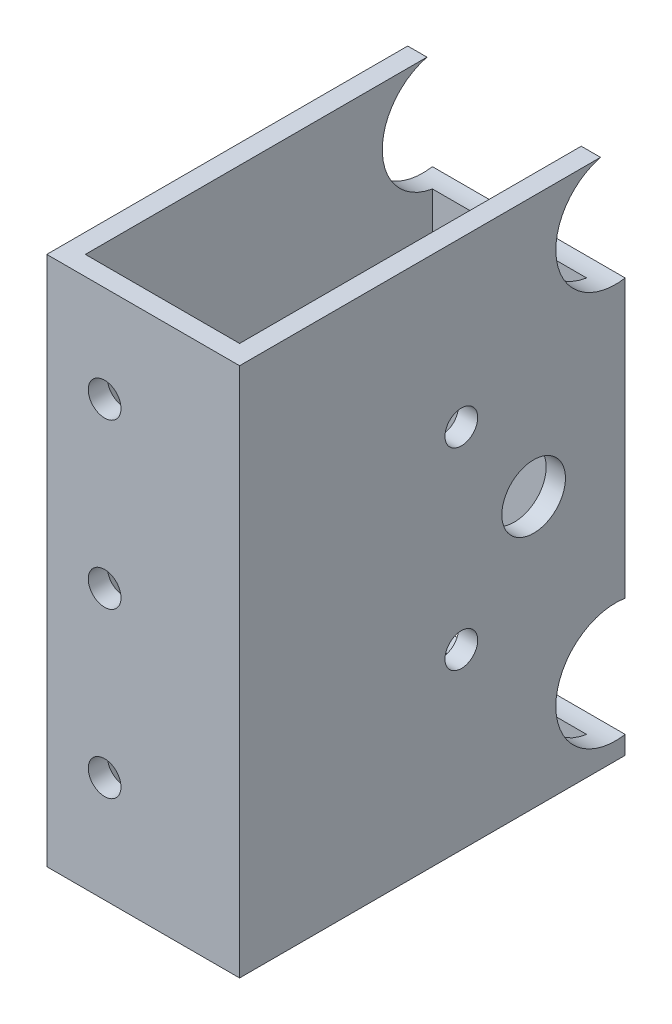
SolidWorks part; units mm, degrees
other "Preload Steel Carriage Core"
other "Preload Steel Carriage Core Left"
ref_plane "Front Plane" through (0, 0, 0) normal (0, 0, 1) x (1, 0, 0)
ref_plane "Top Plane" through (0, 0, 0) normal (0, 1, 0) x (1, 0, 0)
ref_plane "Right Plane" through (0, 0, 0) normal (1, 0, 0) x (0, 0, -1)
sketch3d "Steel tube stock sketch datum points"
  point P0 (29.7083, -56, -29)
  point P1 (39.7083, -56, -29)
  point P2 (29.7083, -46, -29)
ref_plane "Steel tube stock sketch plane" through (0, 0, -29) normal (0, 0, 1) x (1, 0, 0)
sketch "Steel tube stock sketch" plane through (0, 0, -29) normal (0, 0, 1) x (1, 0, 0)
  line L0 (29.7083, -56) -> (49.7083, -56)
  line L1 (49.7083, -56) -> (49.7083, -1)
  line L2 (49.7083, -1) -> (29.7083, -1)
  line L3 (29.7083, -1) -> (29.7083, -56)
extrude "Steel tube stock" add sketch "Steel tube stock sketch" along normal blind 40 separate body
sketch3d "Tube interior sketch datum points"
  point P0 (31.7083, -56.1, -27)
  point P1 (41.7083, -56.1, -27)
  point P2 (31.7083, -46.1, -27)
ref_plane "Tube interior sketch plane" through (0, 0, -27) normal (0, 0, 1) x (1, 0, 0)
sketch "Tube interior sketch" plane through (0, 0, -27) normal (0, 0, 1) x (1, 0, 0)
  line L0 (31.7083, -56.1) -> (47.7083, -56.1)
  line L1 (47.7083, -56.1) -> (47.7083, -0.9)
  line L2 (47.7083, -0.9) -> (31.7083, -0.9)
  line L3 (31.7083, -0.9) -> (31.7083, -56.1)
extrude "Tube interior" cut sketch "Tube interior sketch" along normal blind 36
sketch3d "Guide bush clearance 1 sketch datum points"
  point P0 (29.6, -9, -28)
  point P1 (29.6, 1, -28)
  point P2 (29.6, -9, -18)
ref_plane "Guide bush clearance 1 sketch plane" through (29.6, 0, 0) normal (1, 0, 0) x (0, 0, -1)
sketch "Guide bush clearance 1 sketch" plane through (29.6, 0, 0) normal (1, 0, 0) x (0, 0, -1)
  circle A0 centre (28, -9) radius 6.2
extrude "Guide bush clearance 1" cut sketch "Guide bush clearance 1 sketch" along normal blind 20.3
sketch3d "Guide bush clearance 2 sketch datum points"
  point P0 (29.6, -50, -28)
  point P1 (29.6, -40, -28)
  point P2 (29.6, -50, -18)
ref_plane "Guide bush clearance 2 sketch plane" through (29.6, 0, 0) normal (1, 0, 0) x (0, 0, -1)
sketch "Guide bush clearance 2 sketch" plane through (29.6, 0, 0) normal (1, 0, 0) x (0, 0, -1)
  circle A0 centre (28, -50) radius 6.2
extrude "Guide bush clearance 2" cut sketch "Guide bush clearance 2 sketch" along normal blind 20.3
sketch3d "Screw through clearance sketch datum points"
  point P0 (29.6, -29, -19.5)
  point P1 (29.6, -19, -19.5)
  point P2 (29.6, -29, -9.5)
ref_plane "Screw through clearance sketch plane" through (29.6, 0, 0) normal (1, 0, 0) x (0, 0, -1)
sketch "Screw through clearance sketch" plane through (29.6, 0, 0) normal (1, 0, 0) x (0, 0, -1)
  circle A0 centre (19.5, -29) radius 3.3
extrude "Screw through clearance" cut sketch "Screw through clearance sketch" along normal blind 20.3
sketch3d "Spring pin clearance 1 sketch datum points"
  point P0 (35.7083, -12, 8.9)
  point P1 (45.7083, -12, 8.9)
  point P2 (35.7083, -2, 8.9)
ref_plane "Spring pin clearance 1 sketch plane" through (0, 0, 8.9) normal (0, 0, 1) x (1, 0, 0)
sketch "Spring pin clearance 1 sketch" plane through (0, 0, 8.9) normal (0, 0, 1) x (1, 0, 0)
  circle A0 centre (35.7083, -12) radius 1.7
extrude "Spring pin clearance 1" cut sketch "Spring pin clearance 1 sketch" along normal blind 2.2
sketch3d "Spring pin clearance 2 sketch datum points"
  point P0 (35.7083, -29, 8.9)
  point P1 (45.7083, -29, 8.9)
  point P2 (35.7083, -19, 8.9)
ref_plane "Spring pin clearance 2 sketch plane" through (0, 0, 8.9) normal (0, 0, 1) x (1, 0, 0)
sketch "Spring pin clearance 2 sketch" plane through (0, 0, 8.9) normal (0, 0, 1) x (1, 0, 0)
  circle A0 centre (35.7083, -29) radius 1.7
extrude "Spring pin clearance 2" cut sketch "Spring pin clearance 2 sketch" along normal blind 2.2
sketch3d "Spring pin clearance 3 sketch datum points"
  point P0 (35.7083, -46, 8.9)
  point P1 (45.7083, -46, 8.9)
  point P2 (35.7083, -36, 8.9)
ref_plane "Spring pin clearance 3 sketch plane" through (0, 0, 8.9) normal (0, 0, 1) x (1, 0, 0)
sketch "Spring pin clearance 3 sketch" plane through (0, 0, 8.9) normal (0, 0, 1) x (1, 0, 0)
  circle A0 centre (35.7083, -46) radius 1.7
extrude "Spring pin clearance 3" cut sketch "Spring pin clearance 3 sketch" along normal blind 2.2
sketch3d "Clamp bolt clearance 1 sketch datum points"
  point P0 (47.6, -19, -12)
  point P1 (47.6, -9, -12)
  point P2 (47.6, -19, -2)
ref_plane "Clamp bolt clearance 1 sketch plane" through (47.6, 0, 0) normal (1, 0, 0) x (0, 0, -1)
sketch "Clamp bolt clearance 1 sketch" plane through (47.6, 0, 0) normal (1, 0, 0) x (0, 0, -1)
  circle A0 centre (12, -19) radius 1.7
extrude "Clamp bolt clearance 1" cut sketch "Clamp bolt clearance 1 sketch" along normal blind 2.3
sketch3d "Clamp bolt clearance 2 sketch datum points"
  point P0 (47.6, -39, -12)
  point P1 (47.6, -29, -12)
  point P2 (47.6, -39, -2)
ref_plane "Clamp bolt clearance 2 sketch plane" through (47.6, 0, 0) normal (1, 0, 0) x (0, 0, -1)
sketch "Clamp bolt clearance 2 sketch" plane through (47.6, 0, 0) normal (1, 0, 0) x (0, 0, -1)
  circle A0 centre (12, -39) radius 1.7
extrude "Clamp bolt clearance 2" cut sketch "Clamp bolt clearance 2 sketch" along normal blind 2.3
sketch3d "Mirror1 profile datum points"
  point P0 (0, 0, 0)
  point P1 (10, 0, 0)
  point P2 (0, 0, 10)
ref_plane "Mirror1 profile plane" through (0, 0, 0) normal (0, -1, 0) x (-1, 0, 0)
mirror "Mirror1" about plane through (0, 0, 0) normal (0, -1, 0) of bodies 110
delete or keep bodies "Remove1" type delete bodies bodies 110
